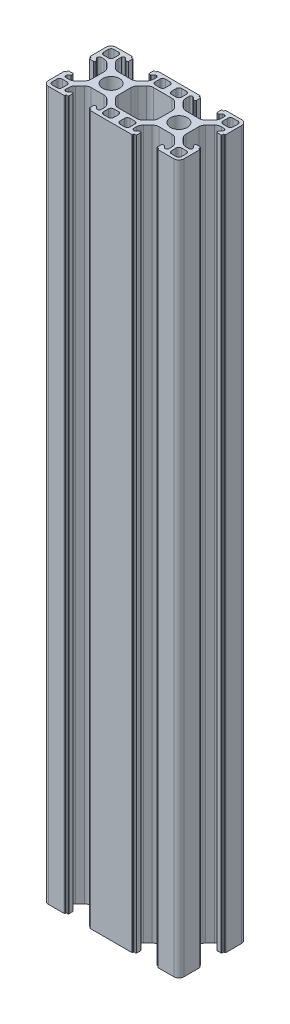
SolidWorks part; units mm, degrees
ref_plane "Спереди" through (0, 0, 0) normal (0, 0, 1) x (1, 0, 0)
ref_plane "Сверху" through (0, 0, 0) normal (0, 1, 0) x (1, 0, 0)
ref_plane "Справа" through (0, 0, 0) normal (1, 0, 0) x (0, 0, -1)
sketch "Эскиз1" plane through (0, 0, 0) normal (0, 1, 0) x (1, 0, 0)
  line L0 (-3.1522, 8.2837) -> (-1.6522, 6.7837) construction
  line L1 (18.3478, 9.7837) -> (15.3478, 6.7837) construction
  line L2 (-10.7522, 0.6837) -> (-0.7522, 10.6837) construction
  line L3 (9.2478, 4.6837) -> (11.1466, 4.6837)
  line L4 (9.2478, 0.6837) -> (19.2478, 10.6837) construction
  line L5 (16.8478, 8.2837) -> (15.3478, 9.7837) construction
  line L6 (12.5608, 5.2695) -> (13.862, 6.5707)
  line L7 (16.1478, 6.7837) -> (17.5478, 6.7837)
  line L8 (15.3478, 7.5837) -> (15.3478, 8.9837)
  line L9 (17.5478, 9.7837) -> (16.1478, 9.7837)
  line L10 (14.4478, 8.8837) -> (14.4478, 7.9849)
  line L11 (13.011, 8.757) -> (13.4914, 9.2373)
  line L12 (12.4478, 10.2328) -> (12.9478, 10.2328)
  line L13 (12.8343, 8.6837) -> (12.5478, 8.6837)
  line L14 (13.8449, 9.3837) -> (13.9478, 9.3837)
  line L15 (12.9478, 10.5337) -> (12.9478, 10.2328)
  line L16 (12.2978, 10.0828) -> (12.2978, 8.9337)
  line L17 (17.7478, 10.6837) -> (13.0978, 10.6837)
  line L18 (18.3478, 8.9837) -> (18.3478, 7.5837)
  line L19 (19.2478, 9.1837) -> (19.2478, 4.5337)
  line L20 (18.6469, 3.7337) -> (17.4978, 3.7337)
  line L21 (19.0978, 4.3837) -> (18.7969, 4.3837)
  line L22 (17.9478, 5.2808) -> (17.9478, 5.3837)
  line L23 (17.2478, 4.2702) -> (17.2478, 3.9837)
  line L24 (18.7969, 3.8837) -> (18.7969, 4.3837)
  line L25 (17.321, 4.447) -> (17.8014, 4.9273)
  line L26 (17.4478, 5.8837) -> (16.549, 5.8837)
  line L27 (13.8336, 3.9967) -> (15.1348, 5.2979)
  line L28 (13.2478, 0.6837) -> (13.2478, 2.5825)
  line L29 (13.2478, 0.6837) -> (13.2478, -1.2151)
  line L30 (13.8336, -2.6293) -> (15.1348, -3.9305)
  line L31 (15.3478, -6.2163) -> (15.3478, -7.6163)
  line L32 (16.1478, -5.4163) -> (17.5478, -5.4163)
  line L33 (18.3478, -7.6163) -> (18.3478, -6.2163)
  line L34 (17.4478, -4.5163) -> (16.549, -4.5163)
  line L35 (17.321, -3.0795) -> (17.8014, -3.5598)
  line L36 (18.7969, -2.5163) -> (18.7969, -3.0163)
  line L37 (17.2478, -2.9027) -> (17.2478, -2.6163)
  line L38 (17.9478, -3.9134) -> (17.9478, -4.0163)
  line L39 (19.0978, -3.0163) -> (18.7969, -3.0163)
  line L40 (18.6469, -2.3663) -> (17.4978, -2.3663)
  line L41 (19.2478, -7.8163) -> (19.2478, -3.1663)
  line L42 (17.5478, -8.4163) -> (16.1478, -8.4163)
  line L43 (17.7478, -9.3163) -> (13.0978, -9.3163)
  line L44 (12.2978, -8.7153) -> (12.2978, -7.5663)
  line L45 (12.9478, -9.1663) -> (12.9478, -8.8653)
  line L46 (13.8449, -8.0163) -> (13.9478, -8.0163)
  line L47 (12.8343, -7.3163) -> (12.5478, -7.3163)
  line L48 (12.4478, -8.8653) -> (12.9478, -8.8653)
  line L49 (13.011, -7.3895) -> (13.4914, -7.8698)
  line L50 (14.4478, -7.5163) -> (14.4478, -6.6175)
  line L51 (12.5608, -3.9021) -> (13.862, -5.2033)
  line L52 (9.2478, -3.3163) -> (11.1466, -3.3163)
  line L53 (18.3478, -8.4163) -> (15.3478, -5.4163) construction
  line L54 (9.2478, 0.6837) -> (19.2478, -9.3163) construction
  line L55 (16.8478, -6.9163) -> (18.3478, -5.4163) construction
  line L56 (9.2478, -3.3163) -> (7.349, -3.3163)
  line L57 (5.9348, -3.9021) -> (4.6336, -5.2033)
  line L58 (2.3478, -5.4163) -> (0.9478, -5.4163)
  line L59 (3.1478, -6.2163) -> (3.1478, -7.6163)
  line L60 (0.9478, -8.4163) -> (2.3478, -8.4163)
  line L61 (4.0478, -7.5163) -> (4.0478, -6.6175)
  line L62 (5.4846, -7.3895) -> (5.0043, -7.8698)
  line L63 (6.0478, -8.8653) -> (5.5478, -8.8653)
  line L64 (5.6614, -7.3163) -> (5.9478, -7.3163)
  line L65 (4.6507, -8.0163) -> (4.5478, -8.0163)
  line L66 (5.5478, -9.1663) -> (5.5478, -8.8653)
  line L67 (6.1978, -8.7153) -> (6.1978, -7.5663)
  line L68 (0.7478, -9.3163) -> (5.3978, -9.3163)
  line L69 (0.1478, -7.6163) -> (0.1478, -6.2163)
  line L70 (1.0478, -4.5163) -> (1.9466, -4.5163)
  line L71 (4.662, -2.6293) -> (3.3608, -3.9305)
  line L72 (5.2478, 0.6837) -> (5.2478, -1.2151)
  line L73 (-1.6522, 9.7837) -> (-4.6522, 6.7837) construction
  line L74 (0.1478, -8.4163) -> (3.1478, -5.4163) construction
  line L75 (-3.1522, -6.9163) -> (-4.6522, -8.4163) construction
  line L76 (9.2478, 0.6837) -> (-0.7522, -9.3163) construction
  line L77 (1.6478, -6.9163) -> (3.1478, -8.4163) construction
  line L78 (5.2478, 0.6837) -> (5.2478, 2.5825)
  line L79 (4.662, 3.9967) -> (3.3608, 5.2979)
  line L80 (3.1478, 7.5837) -> (3.1478, 8.9837)
  line L81 (2.3478, 6.7837) -> (0.9478, 6.7837)
  line L82 (0.1478, 8.9837) -> (0.1478, 7.5837)
  line L83 (1.0478, 5.8837) -> (1.9466, 5.8837)
  line L84 (0.9478, 9.7837) -> (2.3478, 9.7837)
  line L85 (0.7478, 10.6837) -> (5.3978, 10.6837)
  line L86 (6.1978, 10.0828) -> (6.1978, 8.9337)
  line L87 (5.5478, 10.5337) -> (5.5478, 10.2328)
  line L88 (4.6507, 9.3837) -> (4.5478, 9.3837)
  line L89 (5.6614, 8.6837) -> (5.9478, 8.6837)
  line L90 (6.0478, 10.2328) -> (5.5478, 10.2328)
  line L91 (5.4846, 8.757) -> (5.0043, 9.2373)
  line L92 (4.0478, 8.8837) -> (4.0478, 7.9849)
  line L93 (5.9348, 5.2695) -> (4.6336, 6.5707)
  line L94 (9.2478, 4.6837) -> (7.349, 4.6837)
  line L95 (-2.5162, 0.6837) -> (20.7522, 0.6837) construction
  line L96 (0.1478, 9.7837) -> (3.1478, 6.7837) construction
  line L97 (9.2478, -11.4027) -> (9.2478, 11.4027) construction
  line L98 (9.2478, 0.6837) -> (-0.7522, 10.6837) construction
  line L99 (1.6478, 8.2837) -> (0.1478, 6.7837) construction
  line L100 (-10.7522, 0.6837) -> (-0.7522, -9.3163) construction
  line L101 (-1.6522, -8.4163) -> (-4.6522, -5.4163) construction
  line L102 (-18.3522, -6.9163) -> (-19.8522, -5.4163) construction
  line L103 (-10.7522, 0.6837) -> (-20.7522, -9.3163) construction
  line L104 (-19.8522, -8.4163) -> (-16.8522, -5.4163) construction
  line L105 (-18.3522, 8.2837) -> (-16.8522, 9.7837) construction
  line L106 (-10.7522, 0.6837) -> (-20.7522, 10.6837) construction
  line L107 (-19.8522, 9.7837) -> (-16.8522, 6.7837) construction
  line L108 (-10.7522, 4.6837) -> (-8.8534, 4.6837)
  line L109 (-7.4392, 5.2695) -> (-6.138, 6.5707)
  line L110 (-5.5522, 8.8837) -> (-5.5522, 7.9849)
  line L111 (-6.989, 8.757) -> (-6.5086, 9.2373)
  line L112 (-7.5522, 10.2328) -> (-7.0522, 10.2328)
  line L113 (-7.1657, 8.6837) -> (-7.4522, 8.6837)
  line L114 (-6.1551, 9.3837) -> (-6.0522, 9.3837)
  line L115 (-7.0522, 10.5337) -> (-7.0522, 10.2328)
  line L116 (-7.7022, 10.0828) -> (-7.7022, 8.9337)
  line L117 (-2.2522, 10.6837) -> (-6.9022, 10.6837)
  line L118 (-2.4522, 9.7837) -> (-3.8522, 9.7837)
  line L119 (-2.5522, 5.8837) -> (-3.451, 5.8837)
  line L120 (-1.6522, 8.9837) -> (-1.6522, 7.5837)
  line L121 (-3.8522, 6.7837) -> (-2.4522, 6.7837)
  line L122 (-4.6522, 7.5837) -> (-4.6522, 8.9837)
  line L123 (-6.1664, 3.9967) -> (-4.8652, 5.2979)
  line L124 (-6.7522, 0.6837) -> (-6.7522, 2.5825)
  line L125 (-6.7522, 0.6837) -> (-6.7522, -1.2151)
  line L126 (-6.1664, -2.6293) -> (-4.8652, -3.9305)
  line L127 (-2.5522, -4.5163) -> (-3.451, -4.5163)
  line L128 (-1.6522, -7.6163) -> (-1.6522, -6.2163)
  line L129 (-2.2522, -9.3163) -> (-6.9022, -9.3163)
  line L130 (-7.7022, -8.7153) -> (-7.7022, -7.5663)
  line L131 (-7.0522, -9.1663) -> (-7.0522, -8.8653)
  line L132 (-6.1551, -8.0163) -> (-6.0522, -8.0163)
  line L133 (-7.1657, -7.3163) -> (-7.4522, -7.3163)
  line L134 (-7.5522, -8.8653) -> (-7.0522, -8.8653)
  line L135 (-6.989, -7.3895) -> (-6.5086, -7.8698)
  line L136 (-5.5522, -7.5163) -> (-5.5522, -6.6175)
  line L137 (-2.4522, -8.4163) -> (-3.8522, -8.4163)
  line L138 (-4.6522, -6.2163) -> (-4.6522, -7.6163)
  line L139 (-3.8522, -5.4163) -> (-2.4522, -5.4163)
  line L140 (-7.4392, -3.9021) -> (-6.138, -5.2033)
  line L141 (-10.7522, -3.3163) -> (-8.8534, -3.3163)
  line L142 (-10.7522, -3.3163) -> (-12.651, -3.3163)
  line L143 (-14.0652, -3.9021) -> (-15.3664, -5.2033)
  line L144 (-15.9522, -7.5163) -> (-15.9522, -6.6175)
  line L145 (-14.5154, -7.3895) -> (-14.9957, -7.8698)
  line L146 (-13.9522, -8.8653) -> (-14.4522, -8.8653)
  line L147 (-14.3386, -7.3163) -> (-14.0522, -7.3163)
  line L148 (-15.3493, -8.0163) -> (-15.4522, -8.0163)
  line L149 (-14.4522, -9.1663) -> (-14.4522, -8.8653)
  line L150 (-13.8022, -8.7153) -> (-13.8022, -7.5663)
  line L151 (-19.2522, -9.3163) -> (-14.6022, -9.3163)
  line L152 (-19.0522, -8.4163) -> (-17.6522, -8.4163)
  line L153 (-20.7522, -7.8163) -> (-20.7522, -3.1663)
  line L154 (-20.1512, -2.3663) -> (-19.0022, -2.3663)
  line L155 (-20.6022, -3.0163) -> (-20.3012, -3.0163)
  line L156 (-19.4522, -3.9134) -> (-19.4522, -4.0163)
  line L157 (-18.7522, -2.9027) -> (-18.7522, -2.6163)
  line L158 (-20.3012, -2.5163) -> (-20.3012, -3.0163)
  line L159 (-18.8254, -3.0795) -> (-19.3057, -3.5598)
  line L160 (-18.9522, -4.5163) -> (-18.0534, -4.5163)
  line L161 (-19.8522, -7.6163) -> (-19.8522, -6.2163)
  line L162 (-17.6522, -5.4163) -> (-19.0522, -5.4163)
  line L163 (-16.8522, -6.2163) -> (-16.8522, -7.6163)
  line L164 (-15.338, -2.6293) -> (-16.6392, -3.9305)
  line L165 (-14.7522, 0.6837) -> (-14.7522, -1.2151)
  line L166 (-14.7522, 0.6837) -> (-14.7522, 2.5825)
  line L167 (-15.338, 3.9967) -> (-16.6392, 5.2979)
  line L168 (-18.9522, 5.8837) -> (-18.0534, 5.8837)
  line L169 (-18.8254, 4.447) -> (-19.3057, 4.9273)
  line L170 (-20.3012, 3.8837) -> (-20.3012, 4.3837)
  line L171 (-18.7522, 4.2702) -> (-18.7522, 3.9837)
  line L172 (-19.4522, 5.2808) -> (-19.4522, 5.3837)
  line L173 (-20.6022, 4.3837) -> (-20.3012, 4.3837)
  line L174 (-20.1512, 3.7337) -> (-19.0022, 3.7337)
  line L175 (-20.7522, 9.1837) -> (-20.7522, 4.5337)
  line L176 (-19.8522, 8.9837) -> (-19.8522, 7.5837)
  line L177 (-19.2522, 10.6837) -> (-14.6022, 10.6837)
  line L178 (-13.8022, 10.0828) -> (-13.8022, 8.9337)
  line L179 (-14.4522, 10.5337) -> (-14.4522, 10.2328)
  line L180 (-15.3493, 9.3837) -> (-15.4522, 9.3837)
  line L181 (-14.3386, 8.6837) -> (-14.0522, 8.6837)
  line L182 (-13.9522, 10.2328) -> (-14.4522, 10.2328)
  line L183 (-14.5154, 8.757) -> (-14.9957, 9.2373)
  line L184 (-15.9522, 8.8837) -> (-15.9522, 7.9849)
  line L185 (-19.0522, 9.7837) -> (-17.6522, 9.7837)
  line L186 (-16.8522, 7.5837) -> (-16.8522, 8.9837)
  line L187 (-17.6522, 6.7837) -> (-19.0522, 6.7837)
  line L188 (-14.0652, 5.2695) -> (-15.3664, 6.5707)
  line L189 (-10.7522, 4.6837) -> (-12.651, 4.6837)
  line L190 (-2.2522, -9.3163) -> (0.7478, -9.3163)
  line L191 (-2.5522, -4.5163) -> (1.0478, -4.5163)
  line L192 (-2.5522, 5.8837) -> (1.0478, 5.8837)
  line L193 (-2.2522, 10.6837) -> (0.7478, 10.6837)
  arc A0 (18.3478, 8.9837) -> (17.5478, 9.7837) centre (17.5478, 8.9837) ccw
  arc A1 (16.1478, 9.7837) -> (15.3478, 8.9837) centre (16.1478, 8.9837) ccw
  arc A2 (16.1478, 6.7837) -> (15.3478, 7.5837) centre (16.1478, 7.5837) cw
  arc A3 (17.7478, 10.6837) -> (19.2478, 9.1837) centre (17.7478, 9.1837) cw
  arc A4 (12.4478, 10.2328) -> (12.2978, 10.0828) centre (12.4478, 10.0828) ccw
  arc A5 (13.0978, 10.6837) -> (12.9478, 10.5337) centre (13.0978, 10.5337) ccw
  arc A6 (12.8343, 8.6837) -> (13.011, 8.757) centre (12.8343, 8.9337) ccw
  arc A7 (12.5478, 8.6837) -> (12.2978, 8.9337) centre (12.5478, 8.9337) cw
  arc A8 (13.4914, 9.2373) -> (13.8449, 9.3837) centre (13.8449, 8.8837) cw
  arc A9 (13.9478, 9.3837) -> (14.4478, 8.8837) centre (13.9478, 8.8837) cw
  arc A10 (11.7478, 0.6837) -> (9.2478, 3.1837) centre (9.2478, 0.6837) ccw
  arc A11 (11.1466, 4.6837) -> (12.5608, 5.2695) centre (11.1466, 6.6837) ccw
  arc A12 (14.4478, 7.9849) -> (13.862, 6.5707) centre (12.4478, 7.9849) cw
  arc A13 (18.3478, 7.5837) -> (17.5478, 6.7837) centre (17.5478, 7.5837) cw
  arc A14 (17.9478, 5.3837) -> (17.4478, 5.8837) centre (17.4478, 5.3837) ccw
  arc A15 (17.8014, 4.9273) -> (17.9478, 5.2808) centre (17.4478, 5.2808) ccw
  arc A16 (17.2478, 3.9837) -> (17.4978, 3.7337) centre (17.4978, 3.9837) ccw
  arc A17 (17.2478, 4.2702) -> (17.321, 4.447) centre (17.4978, 4.2702) cw
  arc A18 (19.2478, 4.5337) -> (19.0978, 4.3837) centre (19.0978, 4.5337) cw
  arc A19 (18.7969, 3.8837) -> (18.6469, 3.7337) centre (18.6469, 3.8837) cw
  arc A20 (16.549, 5.8837) -> (15.1348, 5.2979) centre (16.549, 3.8837) ccw
  arc A21 (13.2478, 2.5825) -> (13.8336, 3.9967) centre (15.2478, 2.5825) cw
  arc A22 (17.5478, -8.4163) -> (18.3478, -7.6163) centre (17.5478, -7.6163) ccw
  arc A23 (18.3478, -6.2163) -> (17.5478, -5.4163) centre (17.5478, -6.2163) ccw
  arc A24 (15.3478, -6.2163) -> (16.1478, -5.4163) centre (16.1478, -6.2163) cw
  arc A25 (19.2478, -7.8163) -> (17.7478, -9.3163) centre (17.7478, -7.8163) cw
  arc A26 (18.7969, -2.5163) -> (18.6469, -2.3663) centre (18.6469, -2.5163) ccw
  arc A27 (19.2478, -3.1663) -> (19.0978, -3.0163) centre (19.0978, -3.1663) ccw
  arc A28 (17.2478, -2.9027) -> (17.321, -3.0795) centre (17.4978, -2.9027) ccw
  arc A29 (17.2478, -2.6163) -> (17.4978, -2.3663) centre (17.4978, -2.6163) cw
  arc A30 (17.8014, -3.5598) -> (17.9478, -3.9134) centre (17.4478, -3.9134) cw
  arc A31 (17.9478, -4.0163) -> (17.4478, -4.5163) centre (17.4478, -4.0163) cw
  arc A32 (9.2478, -1.8163) -> (11.7478, 0.6837) centre (9.2478, 0.6837) ccw
  arc A33 (13.2478, -1.2151) -> (13.8336, -2.6293) centre (15.2478, -1.2151) ccw
  arc A34 (16.549, -4.5163) -> (15.1348, -3.9305) centre (16.549, -2.5163) cw
  arc A35 (16.1478, -8.4163) -> (15.3478, -7.6163) centre (16.1478, -7.6163) cw
  arc A36 (13.9478, -8.0163) -> (14.4478, -7.5163) centre (13.9478, -7.5163) ccw
  arc A37 (13.4914, -7.8698) -> (13.8449, -8.0163) centre (13.8449, -7.5163) ccw
  arc A38 (12.5478, -7.3163) -> (12.2978, -7.5663) centre (12.5478, -7.5663) ccw
  arc A39 (12.8343, -7.3163) -> (13.011, -7.3895) centre (12.8343, -7.5663) cw
  arc A40 (13.0978, -9.3163) -> (12.9478, -9.1663) centre (13.0978, -9.1663) cw
  arc A41 (12.4478, -8.8653) -> (12.2978, -8.7153) centre (12.4478, -8.7153) cw
  arc A42 (14.4478, -6.6175) -> (13.862, -5.2033) centre (12.4478, -6.6175) ccw
  arc A43 (11.1466, -3.3163) -> (12.5608, -3.9021) centre (11.1466, -5.3163) cw
  arc A44 (0.1478, -7.6163) -> (0.9478, -8.4163) centre (0.9478, -7.6163) ccw
  arc A45 (2.3478, -8.4163) -> (3.1478, -7.6163) centre (2.3478, -7.6163) ccw
  arc A46 (2.3478, -5.4163) -> (3.1478, -6.2163) centre (2.3478, -6.2163) cw
  arc A47 (6.0478, -8.8653) -> (6.1978, -8.7153) centre (6.0478, -8.7153) ccw
  arc A48 (5.3978, -9.3163) -> (5.5478, -9.1663) centre (5.3978, -9.1663) ccw
  arc A49 (5.6614, -7.3163) -> (5.4846, -7.3895) centre (5.6614, -7.5663) ccw
  arc A50 (5.9478, -7.3163) -> (6.1978, -7.5663) centre (5.9478, -7.5663) cw
  arc A51 (5.0043, -7.8698) -> (4.6507, -8.0163) centre (4.6507, -7.5163) cw
  arc A52 (4.5478, -8.0163) -> (4.0478, -7.5163) centre (4.5478, -7.5163) cw
  arc A53 (6.7478, 0.6837) -> (9.2478, -1.8163) centre (9.2478, 0.6837) ccw
  arc A54 (7.349, -3.3163) -> (5.9348, -3.9021) centre (7.349, -5.3163) ccw
  arc A55 (4.0478, -6.6175) -> (4.6336, -5.2033) centre (6.0478, -6.6175) cw
  arc A56 (0.1478, -6.2163) -> (0.9478, -5.4163) centre (0.9478, -6.2163) cw
  arc A57 (1.9466, -4.5163) -> (3.3608, -3.9305) centre (1.9466, -2.5163) ccw
  arc A58 (5.2478, -1.2151) -> (4.662, -2.6293) centre (3.2478, -1.2151) cw
  arc A59 (0.9478, 9.7837) -> (0.1478, 8.9837) centre (0.9478, 8.9837) ccw
  arc A60 (0.1478, 7.5837) -> (0.9478, 6.7837) centre (0.9478, 7.5837) ccw
  arc A61 (3.1478, 7.5837) -> (2.3478, 6.7837) centre (2.3478, 7.5837) cw
  arc A62 (9.2478, 3.1837) -> (6.7478, 0.6837) centre (9.2478, 0.6837) ccw
  arc A63 (5.2478, 2.5825) -> (4.662, 3.9967) centre (3.2478, 2.5825) ccw
  arc A64 (1.9466, 5.8837) -> (3.3608, 5.2979) centre (1.9466, 3.8837) cw
  arc A65 (2.3478, 9.7837) -> (3.1478, 8.9837) centre (2.3478, 8.9837) cw
  arc A66 (4.5478, 9.3837) -> (4.0478, 8.8837) centre (4.5478, 8.8837) ccw
  arc A67 (5.0043, 9.2373) -> (4.6507, 9.3837) centre (4.6507, 8.8837) ccw
  arc A68 (5.9478, 8.6837) -> (6.1978, 8.9337) centre (5.9478, 8.9337) ccw
  arc A69 (5.6614, 8.6837) -> (5.4846, 8.757) centre (5.6614, 8.9337) cw
  arc A70 (5.3978, 10.6837) -> (5.5478, 10.5337) centre (5.3978, 10.5337) cw
  arc A71 (6.0478, 10.2328) -> (6.1978, 10.0828) centre (6.0478, 10.0828) cw
  arc A72 (4.0478, 7.9849) -> (4.6336, 6.5707) centre (6.0478, 7.9849) ccw
  arc A73 (7.349, 4.6837) -> (5.9348, 5.2695) centre (7.349, 6.6837) cw
  arc A74 (-8.8534, 4.6837) -> (-7.4392, 5.2695) centre (-8.8534, 6.6837) ccw
  arc A75 (-5.5522, 7.9849) -> (-6.138, 6.5707) centre (-7.5522, 7.9849) cw
  arc A76 (-7.5522, 10.2328) -> (-7.7022, 10.0828) centre (-7.5522, 10.0828) ccw
  arc A77 (-6.9022, 10.6837) -> (-7.0522, 10.5337) centre (-6.9022, 10.5337) ccw
  arc A78 (-7.1657, 8.6837) -> (-6.989, 8.757) centre (-7.1657, 8.9337) ccw
  arc A79 (-7.4522, 8.6837) -> (-7.7022, 8.9337) centre (-7.4522, 8.9337) cw
  arc A80 (-6.5086, 9.2373) -> (-6.1551, 9.3837) centre (-6.1551, 8.8837) cw
  arc A81 (-6.0522, 9.3837) -> (-5.5522, 8.8837) centre (-6.0522, 8.8837) cw
  arc A82 (-3.8522, 9.7837) -> (-4.6522, 8.9837) centre (-3.8522, 8.9837) ccw
  arc A83 (-3.451, 5.8837) -> (-4.8652, 5.2979) centre (-3.451, 3.8837) ccw
  arc A84 (-6.7522, 2.5825) -> (-6.1664, 3.9967) centre (-4.7522, 2.5825) cw
  arc A85 (-10.7522, 3.1837) -> (-8.2522, 0.6837) centre (-10.7522, 0.6837) cw
  arc A86 (-4.6522, 7.5837) -> (-3.8522, 6.7837) centre (-3.8522, 7.5837) ccw
  arc A87 (-1.6522, 7.5837) -> (-2.4522, 6.7837) centre (-2.4522, 7.5837) cw
  arc A88 (-2.4522, 9.7837) -> (-1.6522, 8.9837) centre (-2.4522, 8.9837) cw
  arc A89 (-6.7522, -1.2151) -> (-6.1664, -2.6293) centre (-4.7522, -1.2151) ccw
  arc A90 (-3.451, -4.5163) -> (-4.8652, -3.9305) centre (-3.451, -2.5163) cw
  arc A91 (-1.6522, -6.2163) -> (-2.4522, -5.4163) centre (-2.4522, -6.2163) ccw
  arc A92 (-5.5522, -6.6175) -> (-6.138, -5.2033) centre (-7.5522, -6.6175) ccw
  arc A93 (-8.8534, -3.3163) -> (-7.4392, -3.9021) centre (-8.8534, -5.3163) cw
  arc A94 (-8.2522, 0.6837) -> (-10.7522, -1.8163) centre (-10.7522, 0.6837) cw
  arc A95 (-6.0522, -8.0163) -> (-5.5522, -7.5163) centre (-6.0522, -7.5163) ccw
  arc A96 (-6.5086, -7.8698) -> (-6.1551, -8.0163) centre (-6.1551, -7.5163) ccw
  arc A97 (-7.4522, -7.3163) -> (-7.7022, -7.5663) centre (-7.4522, -7.5663) ccw
  arc A98 (-7.1657, -7.3163) -> (-6.989, -7.3895) centre (-7.1657, -7.5663) cw
  arc A99 (-6.9022, -9.3163) -> (-7.0522, -9.1663) centre (-6.9022, -9.1663) cw
  arc A100 (-7.5522, -8.8653) -> (-7.7022, -8.7153) centre (-7.5522, -8.7153) cw
  arc A101 (-3.8522, -5.4163) -> (-4.6522, -6.2163) centre (-3.8522, -6.2163) ccw
  arc A102 (-3.8522, -8.4163) -> (-4.6522, -7.6163) centre (-3.8522, -7.6163) cw
  arc A103 (-1.6522, -7.6163) -> (-2.4522, -8.4163) centre (-2.4522, -7.6163) cw
  arc A104 (-12.651, -3.3163) -> (-14.0652, -3.9021) centre (-12.651, -5.3163) ccw
  arc A105 (-15.9522, -6.6175) -> (-15.3664, -5.2033) centre (-13.9522, -6.6175) cw
  arc A106 (-13.9522, -8.8653) -> (-13.8022, -8.7153) centre (-13.9522, -8.7153) ccw
  arc A107 (-14.6022, -9.3163) -> (-14.4522, -9.1663) centre (-14.6022, -9.1663) ccw
  arc A108 (-14.3386, -7.3163) -> (-14.5154, -7.3895) centre (-14.3386, -7.5663) ccw
  arc A109 (-14.0522, -7.3163) -> (-13.8022, -7.5663) centre (-14.0522, -7.5663) cw
  arc A110 (-14.9957, -7.8698) -> (-15.3493, -8.0163) centre (-15.3493, -7.5163) cw
  arc A111 (-15.4522, -8.0163) -> (-15.9522, -7.5163) centre (-15.4522, -7.5163) cw
  arc A112 (-17.6522, -8.4163) -> (-16.8522, -7.6163) centre (-17.6522, -7.6163) ccw
  arc A113 (-18.0534, -4.5163) -> (-16.6392, -3.9305) centre (-18.0534, -2.5163) ccw
  arc A114 (-14.7522, -1.2151) -> (-15.338, -2.6293) centre (-16.7522, -1.2151) cw
  arc A115 (-10.7522, -1.8163) -> (-13.2522, 0.6837) centre (-10.7522, 0.6837) cw
  arc A116 (-19.4522, -4.0163) -> (-18.9522, -4.5163) centre (-18.9522, -4.0163) ccw
  arc A117 (-19.3057, -3.5598) -> (-19.4522, -3.9134) centre (-18.9522, -3.9134) ccw
  arc A118 (-18.7522, -2.6163) -> (-19.0022, -2.3663) centre (-19.0022, -2.6163) ccw
  arc A119 (-18.7522, -2.9027) -> (-18.8254, -3.0795) centre (-19.0022, -2.9027) cw
  arc A120 (-20.7522, -3.1663) -> (-20.6022, -3.0163) centre (-20.6022, -3.1663) cw
  arc A121 (-20.3012, -2.5163) -> (-20.1512, -2.3663) centre (-20.1512, -2.5163) cw
  arc A122 (-20.7522, -7.8163) -> (-19.2522, -9.3163) centre (-19.2522, -7.8163) ccw
  arc A123 (-16.8522, -6.2163) -> (-17.6522, -5.4163) centre (-17.6522, -6.2163) ccw
  arc A124 (-19.8522, -6.2163) -> (-19.0522, -5.4163) centre (-19.0522, -6.2163) cw
  arc A125 (-19.0522, -8.4163) -> (-19.8522, -7.6163) centre (-19.0522, -7.6163) cw
  arc A126 (-14.7522, 2.5825) -> (-15.338, 3.9967) centre (-16.7522, 2.5825) ccw
  arc A127 (-18.0534, 5.8837) -> (-16.6392, 5.2979) centre (-18.0534, 3.8837) cw
  arc A128 (-20.3012, 3.8837) -> (-20.1512, 3.7337) centre (-20.1512, 3.8837) ccw
  arc A129 (-20.7522, 4.5337) -> (-20.6022, 4.3837) centre (-20.6022, 4.5337) ccw
  arc A130 (-18.7522, 4.2702) -> (-18.8254, 4.447) centre (-19.0022, 4.2702) ccw
  arc A131 (-18.7522, 3.9837) -> (-19.0022, 3.7337) centre (-19.0022, 3.9837) cw
  arc A132 (-19.3057, 4.9273) -> (-19.4522, 5.2808) centre (-18.9522, 5.2808) cw
  arc A133 (-19.4522, 5.3837) -> (-18.9522, 5.8837) centre (-18.9522, 5.3837) cw
  arc A134 (-19.8522, 7.5837) -> (-19.0522, 6.7837) centre (-19.0522, 7.5837) ccw
  arc A135 (-15.9522, 7.9849) -> (-15.3664, 6.5707) centre (-13.9522, 7.9849) ccw
  arc A136 (-12.651, 4.6837) -> (-14.0652, 5.2695) centre (-12.651, 6.6837) cw
  arc A137 (-13.2522, 0.6837) -> (-10.7522, 3.1837) centre (-10.7522, 0.6837) cw
  arc A138 (-15.4522, 9.3837) -> (-15.9522, 8.8837) centre (-15.4522, 8.8837) ccw
  arc A139 (-14.9957, 9.2373) -> (-15.3493, 9.3837) centre (-15.3493, 8.8837) ccw
  arc A140 (-14.0522, 8.6837) -> (-13.8022, 8.9337) centre (-14.0522, 8.9337) ccw
  arc A141 (-14.3386, 8.6837) -> (-14.5154, 8.757) centre (-14.3386, 8.9337) cw
  arc A142 (-14.6022, 10.6837) -> (-14.4522, 10.5337) centre (-14.6022, 10.5337) cw
  arc A143 (-13.9522, 10.2328) -> (-13.8022, 10.0828) centre (-13.9522, 10.0828) cw
  arc A144 (-19.2522, 10.6837) -> (-20.7522, 9.1837) centre (-19.2522, 9.1837) ccw
  arc A145 (-17.6522, 6.7837) -> (-16.8522, 7.5837) centre (-17.6522, 7.5837) ccw
  arc A146 (-17.6522, 9.7837) -> (-16.8522, 8.9837) centre (-17.6522, 8.9837) cw
  arc A147 (-19.8522, 8.9837) -> (-19.0522, 9.7837) centre (-19.0522, 8.9837) cw
  point P0 (9.2478, 0.6837)
  point P12 (9.2478, 0.6837)
  point P45 (17.9478, 4.3837)
  point P104 (12.9478, -8.0163)
  point P155 (12.9478, 9.3837)
  point P163 (17.9478, -3.0163)
  point P164 (9.2478, -3.2405)
  point P166 (9.2478, 0.6837)
  point P224 (5.5478, -8.0163)
  point P225 (5.3236, 0.6837)
  point P227 (9.2478, 0.6837)
  point P267 (5.5478, 9.3837)
  point P272 (13.1721, 0.6837)
  point P288 (9.2478, 4.608)
  point P290 (9.2478, 0.6837)
  point P515 (-10.7522, 4.608)
  point P516 (-14.6764, 0.6837)
  point P517 (-7.0522, 9.3837)
  point P518 (-6.8279, 0.6837)
  point P519 (-7.0522, -8.0163)
  point P520 (-10.7522, -3.2405)
  point P521 (-19.4522, -3.0163)
  point P522 (-14.4522, 9.3837)
  point P523 (-14.4522, -8.0163)
  point P524 (-19.4522, 4.3837)
extrude "Бобышка-Вытянуть1" add sketch "Эскиз1" along normal blind 209
